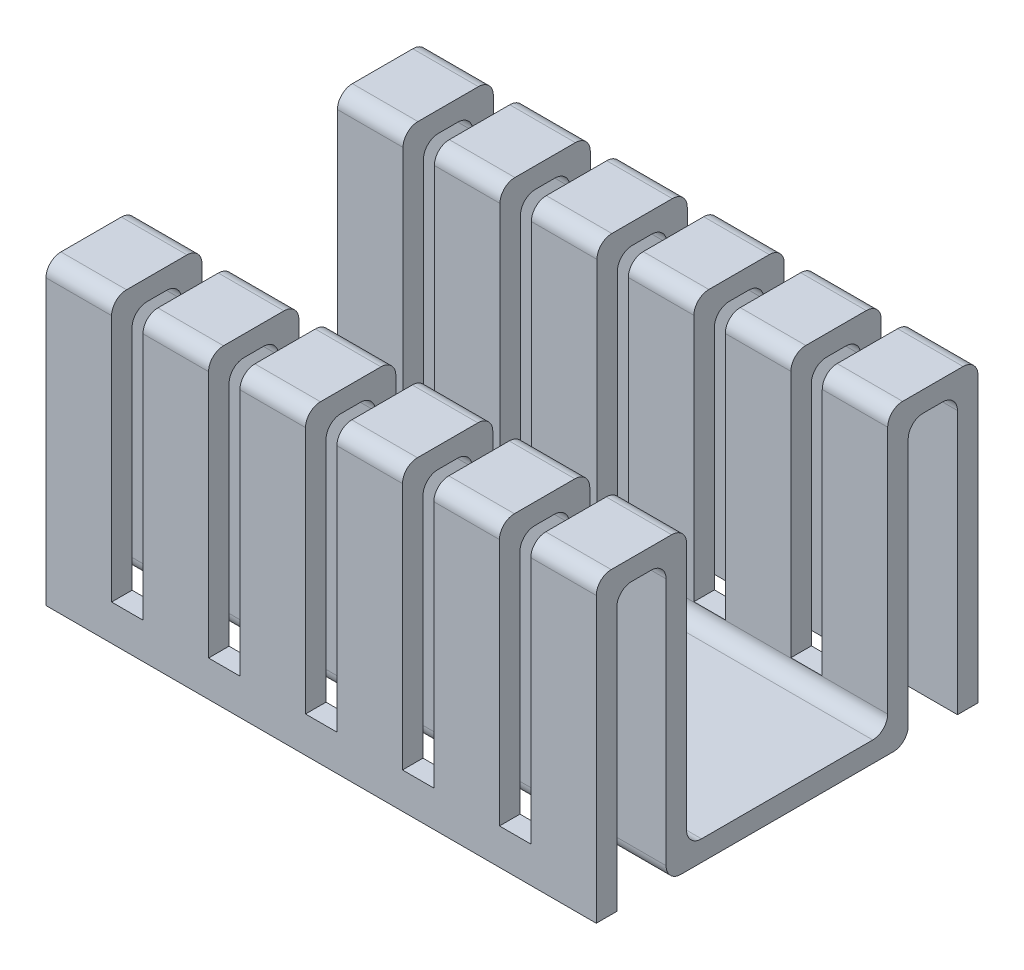
SolidWorks part; units mm, degrees
ref_plane "Front Plane" through (0, 0, 0) normal (0, 0, 1) x (1, 0, 0)
ref_plane "Top Plane" through (0, 0, 0) normal (0, 1, 0) x (1, 0, 0)
ref_plane "Right Plane" through (0, 0, 0) normal (1, 0, 0) x (0, 0, -1)
sketch "Croquis1" plane through (0, 0, 0) normal (1, 0, 0) x (0, 0, -1)
  line L5 (0, 0) -> (0, 19)
  line L9 (-1, 20) -> (-5.045, 20)
  line L10 (0, 0) -> (-1.3725, 0)
  line L11 (-1.3725, 0) -> (-1.3725, 17.6275)
  line L12 (-3.6725, 18.6275) -> (-2.3725, 18.6275)
  line L13 (-4.6725, 17.6275) -> (-4.6725, 1)
  line L14 (-5.6725, 0) -> (-19.8775, 0)
  line L15 (-6.045, 2.3725) -> (-6.045, 19)
  line L16 (-7.045, 1.3725) -> (-18.505, 1.3725)
  line L17 (-6.045, 9.3138) -> (-4.6725, 9.3138) construction
  line L18 (-6.045, 1.3725) -> (-6.045, 0) construction
  line L19 (-3.0225, 20) -> (-3.0225, 18.6275) construction
  line L20 (-12.775, 22.5984) -> (-12.775, -4.8064) construction
  line L21 (-22.5275, 20) -> (-22.5275, 18.6275) construction
  line L22 (-19.505, 1.3725) -> (-19.505, 0) construction
  line L23 (-19.505, 9.3138) -> (-20.8775, 9.3138) construction
  line L24 (-19.505, 2.3725) -> (-19.505, 19)
  line L25 (-20.8775, 17.6275) -> (-20.8775, 1)
  line L26 (-21.8775, 18.6275) -> (-23.1775, 18.6275)
  line L27 (-24.1775, 0) -> (-24.1775, 17.6275)
  line L28 (-25.55, 0) -> (-24.1775, 0)
  line L29 (-24.55, 20) -> (-20.505, 20)
  line L30 (-25.55, 0) -> (-25.55, 19)
  arc A0 (-20.8775, 1) -> (-19.8775, 0) centre (-19.8775, 1) ccw
  arc A1 (-18.505, 1.3725) -> (-19.505, 2.3725) centre (-18.505, 2.3725) cw
  arc A2 (-4.6725, 1) -> (-5.6725, 0) centre (-5.6725, 1) cw
  arc A3 (-6.045, 2.3725) -> (-7.045, 1.3725) centre (-7.045, 2.3725) cw
  arc A4 (-1.3725, 17.6275) -> (-2.3725, 18.6275) centre (-2.3725, 17.6275) ccw
  arc A5 (-3.6725, 18.6275) -> (-4.6725, 17.6275) centre (-3.6725, 17.6275) ccw
  arc A6 (-24.55, 20) -> (-25.55, 19) centre (-24.55, 19) ccw
  arc A7 (-23.1775, 18.6275) -> (-24.1775, 17.6275) centre (-23.1775, 17.6275) ccw
  arc A8 (-20.8775, 17.6275) -> (-21.8775, 18.6275) centre (-21.8775, 17.6275) ccw
  arc A9 (-19.505, 19) -> (-20.505, 20) centre (-20.505, 19) ccw
  arc A10 (-5.045, 20) -> (-6.045, 19) centre (-5.045, 19) ccw
  arc A11 (0, 19) -> (-1, 20) centre (-1, 19) ccw
  point P25 (-12.775, 1.3725)
  point P27 (-12.775, 0)
  point P34 (-20.8775, 0)
  point P40 (-4.6725, 0)
  point P46 (-1.3725, 18.6275)
  point P49 (-4.6725, 18.6275)
  point P52 (-25.55, 20)
  point P55 (-24.1775, 18.6275)
  point P58 (-20.8775, 18.6275)
  point P61 (-19.505, 20)
  point P64 (-6.045, 20)
  point P67 (0, 20)
  dimension "D5" = 1
  dimension "D1" = 25.55
  dimension "D2" = 3.3
  dimension "D3" = 13.46
  dimension "D4" = 20
extrude "Saliente-Extruir1" add sketch "Croquis1" along normal blind 36.83
sketch "Croquis2" plane through (0, 1.3725, 0) normal (0, 1, 0) x (1, 0, 0)
  line L0 (0, -7.82) -> (0, -17.73)
  line L1 (0, -7.045) -> (0, -18.505) construction
  line L2 (0, -17.73) -> (9.91, -17.73)
  line L3 (9.91, -17.73) -> (9.91, -7.82)
  line L4 (8.8819, -12.775) -> (-6.626, -12.775) construction
  line L5 (0, -7.82) -> (9.91, -7.82)
  line L6 (21.28, -12.775) -> (24.96, -12.775) construction
  line L7 (23.12, -14.615) -> (23.12, -10.935) construction
  circle A0 centre (23.12, -12.775) radius 1.84
  point P6 (0, -12.775)
  point P10 (9.91, -12.775)
  point P16 (18.335, -12.775)
  dimension "D4" = 3.68
  dimension "D1" = 4.955
  dimension "D2" = 9.91
  dimension "D3" = 13.21
extrude "Cortar-Extruir1" cut sketch "Croquis2" against normal through all
sketch "Croquis3" plane through (0, 0, 25.55) normal (0, 0, 1) x (1, 0, 0)
  line L0 (4.39, 20) -> (6.49, 20)
  line L1 (36.83, 20) -> (0, 20) construction
  line L2 (4.39, 20) -> (4.39, 2.4)
  line L3 (4.39, 2.4) -> (6.49, 2.4)
  line L4 (6.49, 2.4) -> (6.49, 20)
  line L5 (36.83, 0) -> (0, 0) construction
  line L6 (10.88, 20) -> (10.88, 2.4)
  line L7 (10.88, 20) -> (12.98, 20)
  line L8 (12.98, 2.4) -> (12.98, 20)
  line L9 (10.88, 2.4) -> (12.98, 2.4)
  line L10 (17.37, 20) -> (17.37, 2.4)
  line L11 (17.37, 20) -> (19.47, 20)
  line L12 (19.47, 2.4) -> (19.47, 20)
  line L13 (17.37, 2.4) -> (19.47, 2.4)
  line L14 (23.86, 20) -> (23.86, 2.4)
  line L15 (23.86, 20) -> (25.96, 20)
  line L16 (25.96, 2.4) -> (25.96, 20)
  line L17 (23.86, 2.4) -> (25.96, 2.4)
  line L18 (30.35, 20) -> (30.35, 2.4)
  line L19 (30.35, 20) -> (32.45, 20)
  line L20 (32.45, 2.4) -> (32.45, 20)
  line L21 (30.35, 2.4) -> (32.45, 2.4)
  line L22 (0, 20) -> (4.39, 20) construction
  line L23 (6.49, 20) -> (10.88, 20) construction
  dimension "D1" = 2.1
  dimension "D2" = 4.39
  dimension "D3" = 2.4
  dimension "D4" = 5
extrude "Cortar-Extruir2" cut sketch "Croquis3" against normal through all
